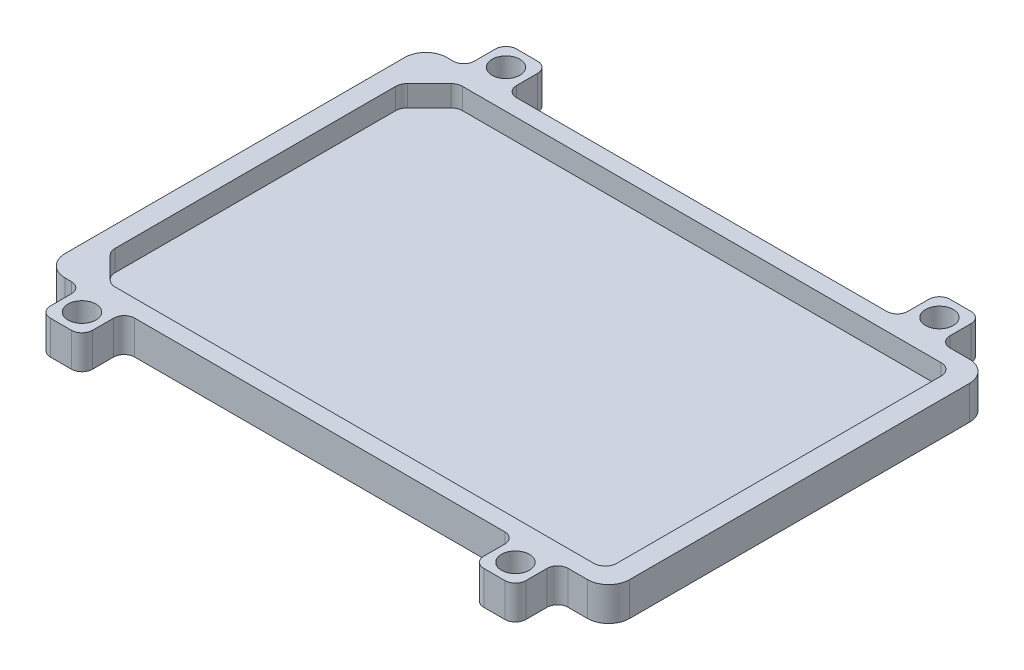
SolidWorks part; units mm, degrees
ref_plane "Front Plane" through (0, 0, 0) normal (0, 0, 1) x (1, 0, 0)
ref_plane "Top Plane" through (0, 0, 0) normal (0, 1, 0) x (1, 0, 0)
ref_plane "Right Plane" through (0, 0, 0) normal (1, 0, 0) x (0, 0, -1)
sketch "Sketch1" plane through (0, 0, 0) normal (0, 1, 0) x (1, 0, 0)
  line L1 (0, 0) -> (157.0786, 0)
  line L2 (0, 0) -> (0, -90.551)
  line L3 (0, -90.551) -> (157.0786, -90.551)
  line L4 (157.0786, 0) -> (157.0786, -90.551)
  dimension "D1" = 157.0786
  dimension "D2" = 90.551
extrude "Boss-Extrude1" add sketch "Sketch1" along normal blind 8
sketch "Sketch7" plane through (0, 0, 0) normal (0, -1, 0) x (1, 0, 0)
  circle A0 centre (33.602, 72.2755) radius 8.95
  circle A1 centre (33.602, 18.2755) radius 8.5
  circle A2 centre (51.692, 72.2755) radius 8.95
  circle A3 centre (69.782, 72.2755) radius 8.95
  circle A4 centre (87.872, 72.2755) radius 8.95
  circle A5 centre (105.962, 72.2755) radius 8.95
  circle A6 centre (124.052, 72.2755) radius 8.95
  circle A7 centre (51.692, 54.2755) radius 8.95
  circle A8 centre (69.782, 54.2755) radius 8.95
  circle A9 centre (87.872, 54.2755) radius 8.95
  circle A10 centre (105.962, 54.2755) radius 8.95
  circle A11 centre (124.052, 54.2755) radius 8.95
  circle A12 centre (51.692, 36.2755) radius 8.95
  circle A13 centre (69.782, 36.2755) radius 8.95
  circle A14 centre (87.872, 36.2755) radius 8.95
  circle A15 centre (105.962, 36.2755) radius 8.95
  circle A16 centre (124.052, 36.2755) radius 8.95
  circle A17 centre (51.692, 18.2755) radius 8.95
  circle A18 centre (69.782, 18.2755) radius 8.95
  circle A19 centre (87.872, 18.2755) radius 8.95
  circle A20 centre (105.962, 18.2755) radius 8.95
  circle A21 centre (124.052, 18.2755) radius 8.95
  circle A22 centre (33.602, 54.2755) radius 8.95
  circle A23 centre (33.602, 36.2755) radius 8.95
  circle A24 centre (33.602, 18.2755) radius 8.95
  circle A25 centre (51.692, 18.2755) radius 8.5
  circle A26 centre (69.782, 18.2755) radius 8.5
  circle A27 centre (87.872, 18.2755) radius 8.5
  circle A28 centre (105.962, 18.2755) radius 8.5
  circle A29 centre (124.052, 18.2755) radius 8.5
  circle A30 centre (33.602, 36.2755) radius 8.5
  circle A31 centre (51.692, 36.2755) radius 8.5
  circle A32 centre (69.782, 36.2755) radius 8.5
  circle A33 centre (87.872, 36.2755) radius 8.5
  circle A34 centre (105.962, 36.2755) radius 8.5
  circle A35 centre (124.052, 36.2755) radius 8.5
  circle A36 centre (33.602, 54.2755) radius 8.5
  circle A37 centre (51.692, 54.2755) radius 8.5
  circle A38 centre (69.782, 54.2755) radius 8.5
  circle A39 centre (87.872, 54.2755) radius 8.5
  circle A40 centre (105.962, 54.2755) radius 8.5
  circle A41 centre (124.052, 54.2755) radius 8.5
  circle A42 centre (124.052, 72.2755) radius 8.5
  circle A43 centre (105.962, 72.2755) radius 8.5
  circle A44 centre (87.872, 72.2755) radius 8.5
  circle A45 centre (69.782, 72.2755) radius 8.5
  circle A46 centre (51.692, 72.2755) radius 8.5
  circle A47 centre (33.602, 72.2755) radius 8.5
  dimension "D1" = 17.9
  dimension "D2" = 17
  dimension "D6" = 18
  dimension "D3" = 18.09
  dimension "D4" = 18
  dimension "D5" = 18.09
  dimension "D7" = 6
  dimension "D8" = 4
sketch "Sketch23" plane through (0, 8, 0) normal (0, 1, 0) x (1, 0, 0)
  line L1 (140.6288, -86.4755) -> (23.2359, -86.4755)
  line L2 (140.6288, -86.4755) -> (140.6288, -4.0755)
  line L3 (140.6288, -4.0755) -> (23.2359, -4.0755)
  line L4 (16.4498, -79.6894) -> (16.4498, -10.8616)
  line L5 (16.4498, -10.8616) -> (23.2359, -4.0755)
  line L6 (23.2359, -4.0755) -> (16.4498, -4.0755) construction
  line L7 (16.4498, -4.0755) -> (16.4498, -10.8616) construction
  line L8 (23.2359, -86.4755) -> (16.4498, -79.6894)
  line L10 (157.0786, 0) -> (0, 0) construction
  line L11 (140.6288, -4.0755) -> (140.6288, 0) construction
  line L12 (23.2359, -86.4755) -> (16.4498, -86.4755) construction
  line L13 (16.4498, -86.4755) -> (16.4498, -79.6894) construction
  line L14 (157.0786, -90.551) -> (157.0786, 0) construction
  line L15 (140.6288, -86.4755) -> (157.0786, -86.4755) construction
  line L16 (16.4498, -86.4755) -> (0, -86.4755) construction
  line L17 (0, 0) -> (0, -90.551) construction
  line L18 (157.0786, 0) -> (0, 0) construction
  line L19 (140.6288, -86.4755) -> (140.6288, -90.551) construction
  line L20 (0, -90.551) -> (157.0786, -90.551) construction
  dimension "D2" = 124.179
  dimension "D3" = 9.597
  dimension "D5" = 9.597
  dimension "D9" = 82.4
  dimension "D10" = 4.0755
extrude "Cut-Extrude21" cut sketch "Sketch23" against normal blind 5
fillet "Fillet8" radius 2.75 6 edges at (140.6288, 5.5, 4.0755) (16.4498, 5.5, 10.8616) (23.2359, 5.5, 4.0755) (140.6288, 5.5, 86.4755) (23.2359, 5.5, 86.4755) (16.4498, 5.5, 79.6894)
sketch "Sketch29" plane through (0, 8, 0) normal (0, 1, 0) x (1, 0, 0)
  line L0 (157.0786, 0) -> (0, 0) construction
  line L1 (157.0786, -90.551) -> (145.4887, -90.551)
  line L2 (157.0786, -90.551) -> (157.0786, 0)
  line L3 (157.0786, 0) -> (145.4887, 0)
  line L4 (145.4887, -90.551) -> (145.4887, 0)
  line L6 (0, -90.551) -> (11.5899, -90.551)
  line L7 (0, -90.551) -> (0, 0)
  line L8 (0, 0) -> (11.5899, 0)
  line L9 (11.5899, -90.551) -> (11.5899, 0)
  dimension "D2" = 4.0755
extrude "Cut-Extrude25" cut sketch "Sketch29" against normal through all
fillet "Fillet9" radius 5 4 edges at (145.4887, 4, 90.551) (145.4887, 4, 0) (11.5899, 4, 90.551) (11.5899, 4, 0)
sketch "Sketch36" plane through (0, 0, 0) normal (0, -1, 0) x (1, 0, 0)
  line L0 (16.5899, 90.551) -> (140.4887, 90.551) construction
  line L1 (20.6082, 90.551) -> (30.6082, 90.551)
  line L2 (20.6082, 90.551) -> (20.6082, 100.551)
  line L3 (20.6082, 100.551) -> (30.6082, 100.551)
  line L4 (30.6082, 90.551) -> (30.6082, 100.551)
  line L5 (140.4887, 0) -> (16.5899, 0) construction
  line L6 (123.3943, 90.551) -> (133.3943, 90.551)
  line L7 (123.3943, 90.551) -> (123.3943, 100.551)
  line L8 (123.3943, 100.551) -> (133.3943, 100.551)
  line L9 (133.3943, 90.551) -> (133.3943, 100.551)
  line L10 (30.6082, 0) -> (20.6082, 0)
  line L11 (30.6082, 0) -> (30.6082, -10)
  line L12 (30.6082, -10) -> (20.6082, -10)
  line L13 (20.6082, 0) -> (20.6082, -10)
  line L14 (11.5899, 85.551) -> (11.5899, 5) construction
  line L15 (123.3943, 0) -> (133.3943, 0)
  line L16 (123.3943, 0) -> (123.3943, -10)
  line L17 (123.3943, -10) -> (133.3943, -10)
  line L18 (133.3943, 0) -> (133.3943, -10)
  line L19 (145.4887, 5) -> (145.4887, 85.551) construction
  line L22 (133.3943, 90.551) -> (123.3943, 100.551) construction
  line L23 (123.3943, 90.551) -> (133.3943, 100.551) construction
  line L24 (30.6082, 100.551) -> (20.6082, 90.551) construction
  line L25 (30.6082, 90.551) -> (20.6082, 100.551) construction
  line L26 (20.6082, 0) -> (30.6082, -10) construction
  line L27 (30.6082, 0) -> (20.6082, -10) construction
  line L28 (20.6082, -10) -> (21.4692, -10.0262) construction
  line L29 (133.3943, 0) -> (123.3943, -10) construction
  line L30 (133.3943, -10) -> (123.3943, 0) construction
  circle A0 centre (128.3943, -5) radius 3.3
  circle A1 centre (25.6082, -5) radius 3.3
  circle A2 centre (25.6082, 95.551) radius 3.3
  circle A3 centre (128.3943, 95.551) radius 3.3
  point P24 (11.5899, 45.2755)
  point P25 (145.4887, 45.2755)
  dimension "D5" = 6.6
  dimension "D9" = 6.6
  dimension "D10" = 7.0944
  dimension "D2" = 102.7861
  dimension "D3" = 10
  dimension "D4" = 10
  dimension "D6" = 4.0183
  dimension "D7" = 4.0183
  dimension "D8" = 7.0944
  dimension "D11" = 102.7861
  dimension "D12" = 14.0183
  dimension "D13" = 17.0944
  dimension "D14" = 133.8987
extrude "Boss-Extrude10" add sketch "Sketch36" against normal up to surface (8 mm away) up to face at (78.5393, 8, 45.2755)
fillet "Fillet10" radius 2.5 16 edges at (20.6082, 4, 100.551) (30.6082, 4, 100.551) (123.3943, 4, 100.551) (133.3943, 4, 100.551) (133.3943, 4, -10) (123.3943, 4, -10) (30.6082, 4, -10) (20.6082, 4, -10) (123.3943, 4, 90.551) (20.6082, 4, 90.551) (133.3943, 4, 90.551) (30.6082, 4, 90.551) (133.3943, 4, 0) (123.3943, 4, 0) (30.6082, 4, 0) (20.6082, 4, 0)
